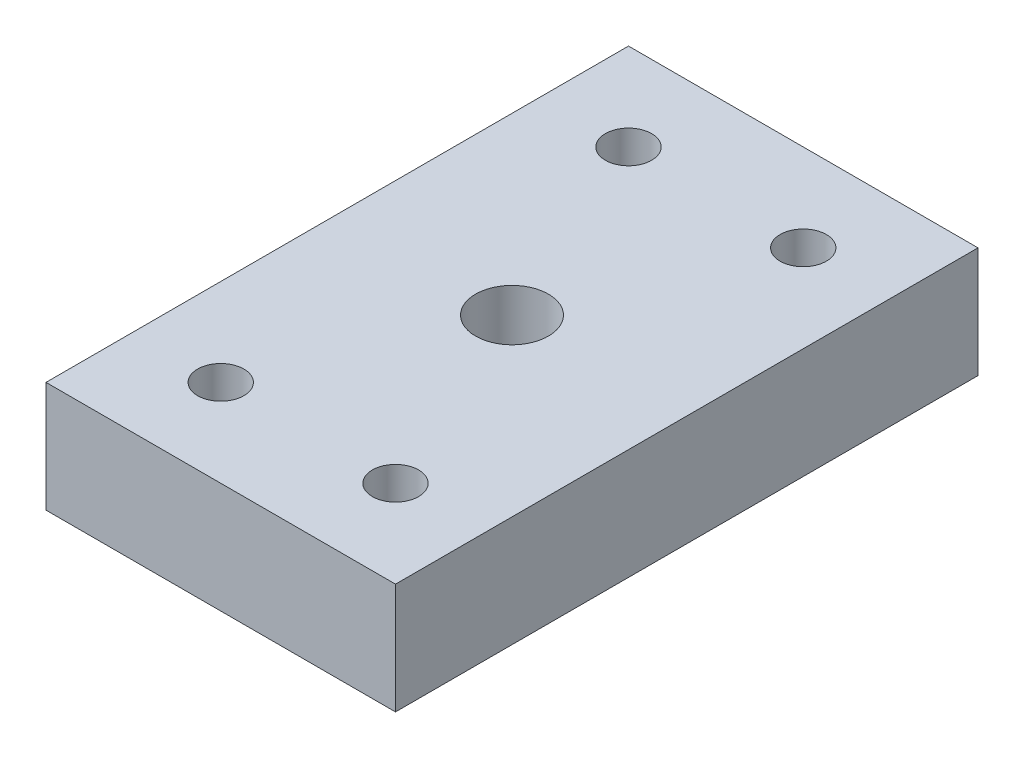
SolidWorks part; units mm, degrees
material "6061 Alloy"
ref_plane "Front Plane" through (0, 0, 0) normal (0, 0, 1) x (1, 0, 0)
ref_plane "Top Plane" through (0, 0, 0) normal (0, 1, 0) x (1, 0, 0)
ref_plane "Right Plane" through (0, 0, 0) normal (1, 0, 0) x (0, 0, -1)
sketch "Sketch1" plane through (0, 0, 0) normal (0, 1, 0) x (1, 0, 0)
  line L1 (-38.1, -63.5) -> (38.1, -63.5)
  line L2 (-38.1, -63.5) -> (-38.1, 63.5)
  line L3 (-38.1, 63.5) -> (38.1, 63.5)
  line L4 (38.1, -63.5) -> (38.1, 63.5)
  line L5 (-38.1, -63.5) -> (38.1, 63.5) construction
  line L6 (-38.1, 63.5) -> (38.1, -63.5) construction
  point P0 (0, 0)
  dimension "D1" = 76.2
  dimension "D2" = 127
extrude "Boss-Extrude1" add sketch "Sketch1" along normal blind 24.13
sketch "Sketch2" plane through (0, 24.13, 0) normal (0, 1, 0) x (1, 0, 0)
  circle A0 centre (0, 0) radius 7.9375
  dimension "D1" = 15.875
extrude "1/2\"-13 Threaded Hole" cut sketch "Sketch2" against normal through all
sketch "Sketch3" plane through (0, 24.13, 0) normal (0, 1, 0) x (1, 0, 0)
  circle A0 centre (-19.05, 44.45) radius 5.0419
  circle A1 centre (19.05, 44.45) radius 5.0419
  circle A2 centre (19.05, -44.45) radius 5.0419
  circle A3 centre (-19.05, -44.45) radius 5.0419
  dimension "D5" = 10.0838
  dimension "D1" = 44.45
  dimension "D2" = 44.45
  dimension "D3" = 19.05
  dimension "D4" = 19.05
extrude "3/8\" Through Holes" cut sketch "Sketch3" against normal through all
